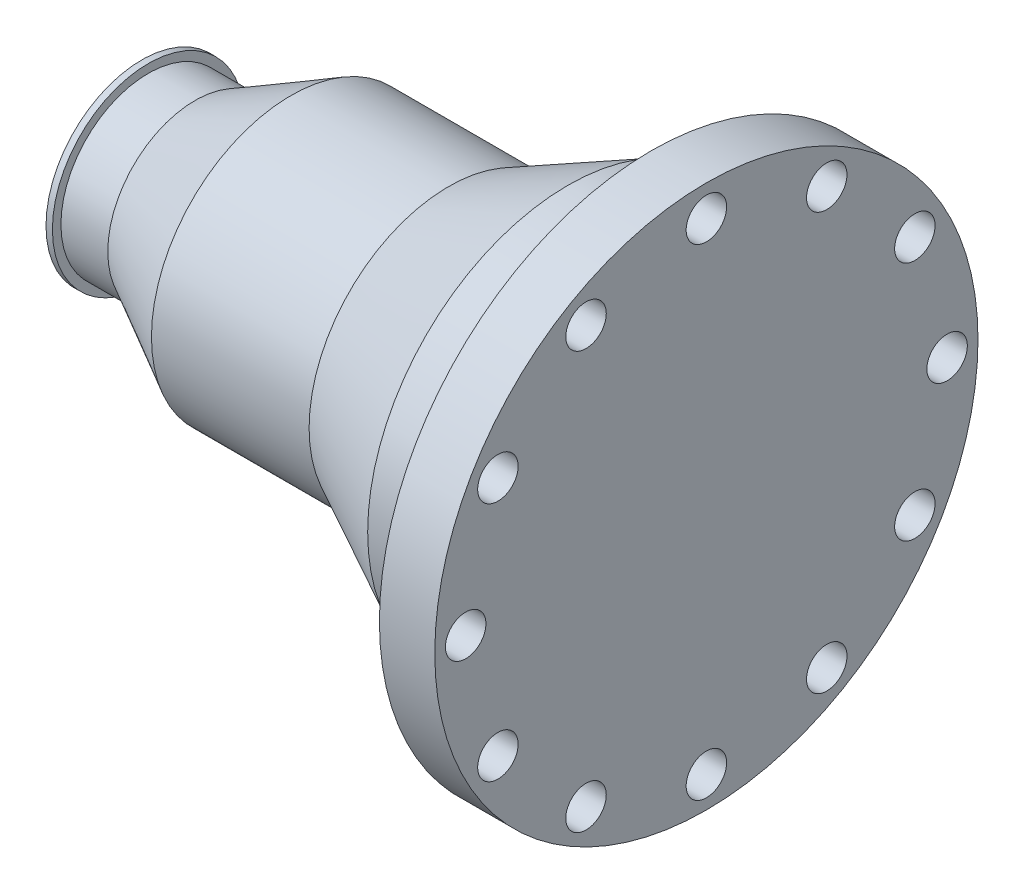
SolidWorks part; units mm, degrees
ref_plane "Спереди" through (0, 0, 0) normal (0, 0, 1) x (1, 0, 0)
ref_plane "Сверху" through (0, 0, 0) normal (0, 1, 0) x (1, 0, 0)
ref_plane "Справа" through (0, 0, 0) normal (1, 0, 0) x (0, 0, -1)
sketch "Эскиз1" plane through (0, 0, 0) normal (0, 0, 1) x (1, 0, 0)
  line L0 (0, 0) -> (265, 0)
  line L1 (0, 0) -> (0, 45)
  line L2 (0, 45) -> (3, 45)
  line L3 (3, 45) -> (3, 41)
  line L4 (3, 41) -> (25, 41)
  line L5 (25, 41) -> (70, 65.5)
  line L6 (70, 65.5) -> (144, 65.5)
  line L7 (144, 65.5) -> (200, 94)
  line L8 (200, 94) -> (220, 94)
  line L9 (220, 94) -> (220, 95)
  line L10 (220, 95) -> (239, 95)
  line L11 (239, 95) -> (239, 100)
  line L12 (239, 100) -> (239, 127.5)
  line L13 (239, 127.5) -> (265, 127.5)
  line L14 (265, 127.5) -> (265, 0)
revolve "Повернуть1" add sketch "Эскиз1" angle 360 about L0
sketch "Эскиз2" plane through (0, 0, 0) normal (0, 0, 1) x (1, 0, 0)
  line L0 (0, 0) -> (257, 0)
  line L1 (0, 0) -> (0, 31)
  line L2 (0, 45) -> (0, -45) construction
  line L3 (0, 31) -> (42, 31)
  line L4 (42, 31) -> (70, 38.5026)
  line L5 (70, 65.5) -> (70, -65.5) construction
  line L6 (90, 52.5) -> (142, 52.5)
  line L7 (143.5, 52.5) -> (146.6699, 52.5)
  line L8 (147.6699, 55) -> (203.5, 55)
  line L9 (203.5, 55) -> (203.5, 47)
  line L10 (203.5, 47) -> (226, 47)
  line L11 (226, 47) -> (239, 34)
  line L12 (239, 95) -> (239, -95) construction
  line L13 (239, 34) -> (257, 34)
  line L14 (257, 34) -> (257, 0)
  arc A0 (70, 38.5026) -> (90, 52.5) centre (107.8022, 5.7765) cw
  arc A1 (142, 52.5) -> (143.5, 52.5) centre (142.75, 49.8032) cw
  arc A2 (146.6699, 52.5) -> (147.6699, 55) centre (147.5934, 53.5806) cw
revolve "Вырез-Повернуть1" cut sketch "Эскиз2" angle 360 about L0
sketch "Эскиз3" plane through (0, 0, 0) normal (1, 0, 0) x (0, 0, -1)
  circle A0 centre (0, 113) radius 9.5
extrude "Вырез-Вытянуть1" cut sketch "Эскиз3" along normal through all
sketch "Эскиз4" plane through (0, 0, 0) normal (1, 0, 0) x (0, 0, -1)
  circle A0 centre (-56.5, 97.8609) radius 9.5
extrude "Вырез-Вытянуть2" cut sketch "Эскиз4" along normal through all
sketch "Эскиз5" plane through (0, 0, 0) normal (1, 0, 0) x (0, 0, -1)
  circle A0 centre (-97.8609, 56.5) radius 9.5
extrude "Вырез-Вытянуть3" cut sketch "Эскиз5" along normal through all
sketch "Эскиз6" plane through (0, 0, 0) normal (1, 0, 0) x (0, 0, -1)
  circle A0 centre (-113, 0) radius 9.5
extrude "Вырез-Вытянуть4" cut sketch "Эскиз6" along normal through all
sketch "Эскиз7" plane through (0, 0, 0) normal (1, 0, 0) x (0, 0, -1)
  circle A0 centre (-97.8609, -56.5) radius 9.5
extrude "Вырез-Вытянуть5" cut sketch "Эскиз7" along normal through all
sketch "Эскиз8" plane through (0, 0, 0) normal (1, 0, 0) x (0, 0, -1)
  circle A0 centre (-56.5, -97.8609) radius 9.5
extrude "Вырез-Вытянуть6" cut sketch "Эскиз8" along normal through all
sketch "Эскиз9" plane through (0, 0, 0) normal (1, 0, 0) x (0, 0, -1)
  circle A0 centre (0, -113) radius 9.5
extrude "Вырез-Вытянуть7" cut sketch "Эскиз9" along normal through all
sketch "Эскиз10" plane through (0, 0, 0) normal (1, 0, 0) x (0, 0, -1)
  circle A0 centre (56.5, -97.8609) radius 9.5
extrude "Вырез-Вытянуть8" cut sketch "Эскиз10" along normal through all
sketch "Эскиз11" plane through (0, 0, 0) normal (1, 0, 0) x (0, 0, -1)
  circle A0 centre (97.8609, -56.5) radius 9.5
extrude "Вырез-Вытянуть9" cut sketch "Эскиз11" along normal through all
sketch "Эскиз12" plane through (0, 0, 0) normal (1, 0, 0) x (0, 0, -1)
  circle A0 centre (113, 0) radius 9.5
extrude "Вырез-Вытянуть10" cut sketch "Эскиз12" along normal through all
sketch "Эскиз13" plane through (0, 0, 0) normal (1, 0, 0) x (0, 0, -1)
  circle A0 centre (97.8609, 56.5) radius 9.5
extrude "Вырез-Вытянуть11" cut sketch "Эскиз13" along normal through all
sketch "Эскиз14" plane through (0, 0, 0) normal (1, 0, 0) x (0, 0, -1)
  circle A0 centre (56.5, 97.8609) radius 9.5
extrude "Вырез-Вытянуть12" cut sketch "Эскиз14" along normal through all
